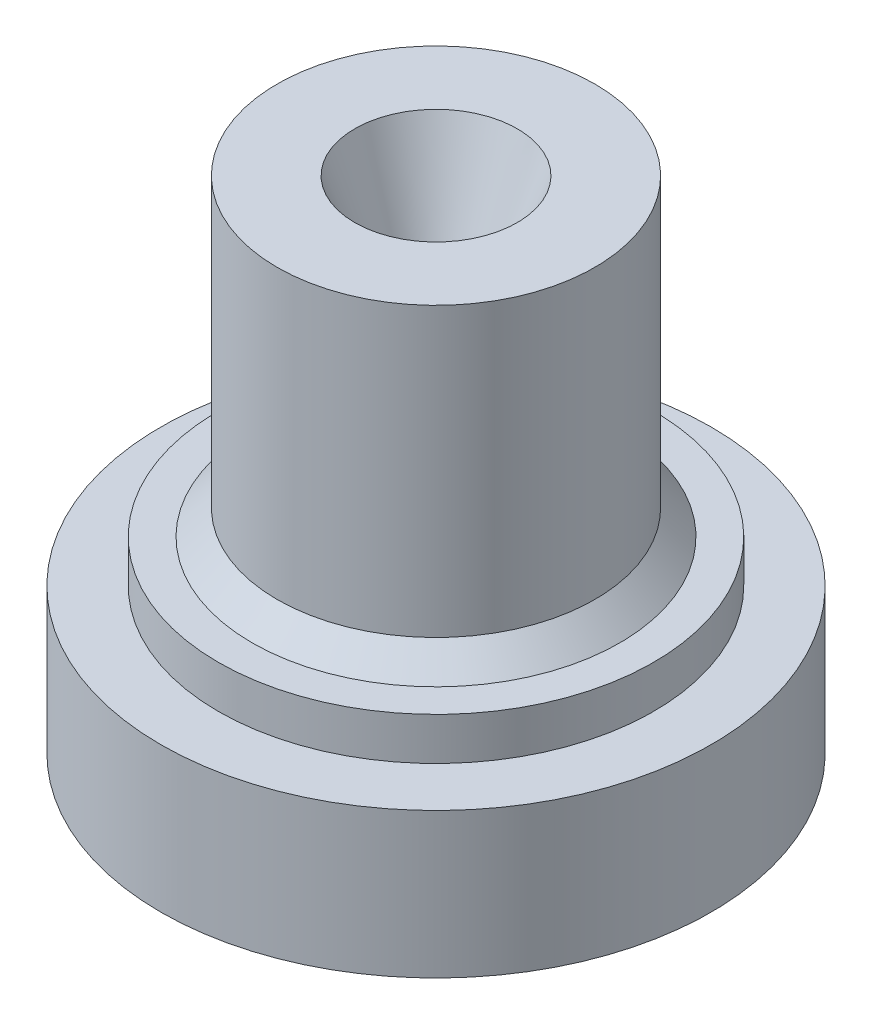
SolidWorks part; units mm, degrees
ref_plane "Front" through (0, 0, 0) normal (0, 0, 1) x (1, 0, 0)
ref_plane "Top" through (0, 0, 0) normal (0, 1, 0) x (1, 0, 0)
ref_plane "Right" through (0, 0, 0) normal (1, 0, 0) x (0, 0, -1)
sketch "Sketch1" plane through (0, 0, 0) normal (0, 1, 0) x (1, 0, 0)
  circle A0 centre (0, 0) radius 11
  dimension "D1" = 22
extrude "Boss-Extrude1" add sketch "Sketch1" along normal blind 5.8
sketch "Sketch2" plane through (0, 5.8, 0) normal (0, 1, 0) x (1, 0, 0)
  circle A0 centre (0, 0) radius 8.7
  dimension "D1" = 17.4
extrude "Boss-Extrude2" add sketch "Sketch2" along normal blind 1.7
sketch "Sketch3" plane through (0, 7.5, 0) normal (0, 1, 0) x (1, 0, 0)
  circle A0 centre (0, 0) radius 6.35
  dimension "D1" = 12.7
extrude "Boss-Extrude3" add sketch "Sketch3" along normal blind 12.5
chamfer "Chamfer1" distance 1 angle 45 1 edges at (0, 7.5, 6.35)
sketch "Sketch4" plane through (0, 20, 0) normal (0, 1, 0) x (1, 0, 0)
  circle A0 centre (0, 0) radius 1.25
  dimension "D1" = 2.5
extrude "Cut-Extrude1" cut sketch "Sketch4" against normal through all
sketch "Sketch5" plane through (0, 20, 0) normal (0, 1, 0) x (1, 0, 0)
  circle A0 centre (0, 0) radius 3.25
  dimension "D1" = 6.5
extrude "Cut-Extrude2" cut sketch "Sketch5" against normal blind 8 draft 20
sketch "Sketch6" plane through (0, 0, 0) normal (0, -1, 0) x (1, 0, 0)
  circle A0 centre (0, 0) radius 10
  dimension "D1" = 20
extrude "Cut-Extrude3" cut sketch "Sketch6" against normal blind 9 draft 45
